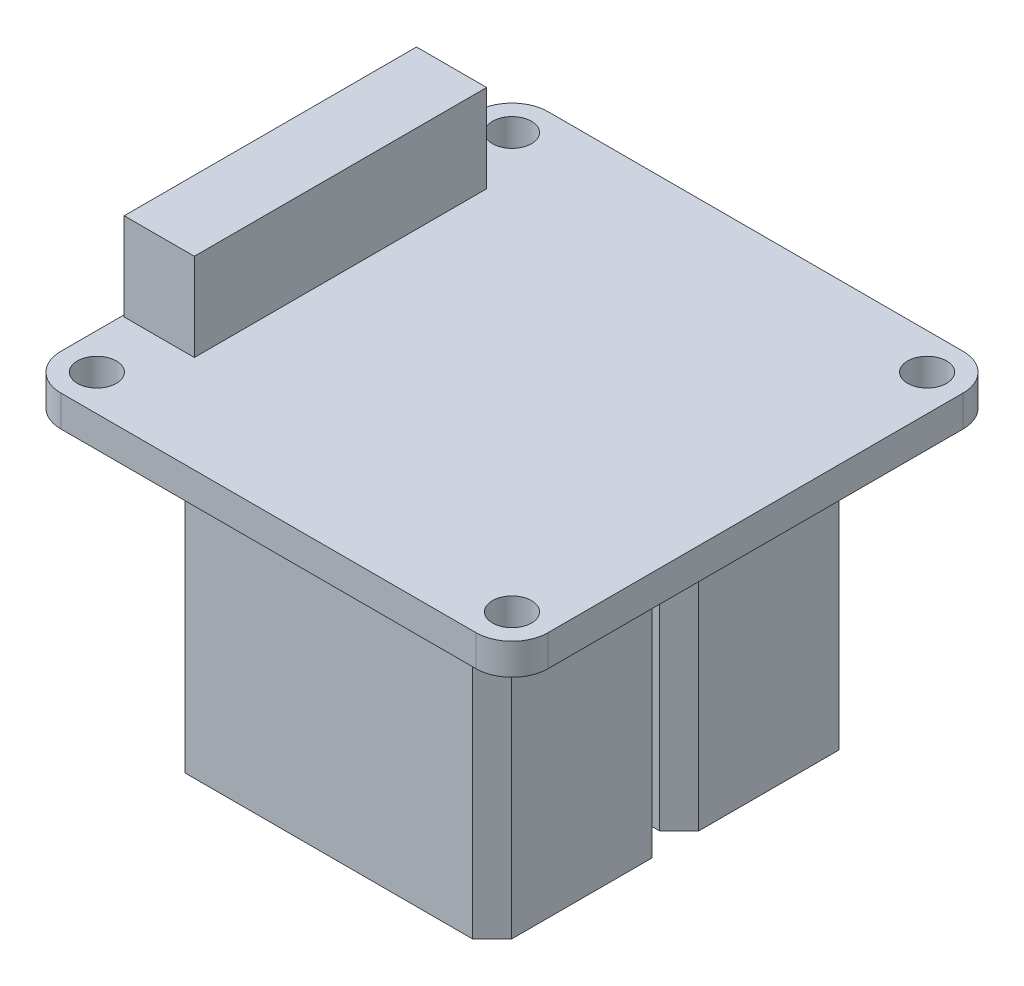
SolidWorks part; units mm, degrees
ref_plane "前视基准面" through (0, 0, 0) normal (0, 0, 1) x (1, 0, 0)
ref_plane "上视基准面" through (0, 0, 0) normal (0, 1, 0) x (1, 0, 0)
ref_plane "右视基准面" through (0, 0, 0) normal (1, 0, 0) x (0, 0, -1)
other "Configuration Table"
sketch "草图1" plane through (0, 0, 0) normal (0, 1, 0) x (1, 0, 0)
  line L1 (-10.65, 12.5) -> (10.65, 12.5)
  line L2 (-12.5, 10.65) -> (-12.5, -10.65)
  line L3 (-10.65, -12.5) -> (10.65, -12.5)
  line L4 (12.5, 10.65) -> (12.5, -10.65)
  line L5 (-12.5, 12.5) -> (12.5, -12.5) construction
  line L6 (-12.5, -12.5) -> (12.5, 12.5) construction
  arc A0 (12.5, 10.65) -> (10.65, 12.5) centre (10.65, 10.65) ccw
  arc A1 (10.65, -12.5) -> (12.5, -10.65) centre (10.65, -10.65) ccw
  arc A2 (-12.5, -10.65) -> (-10.65, -12.5) centre (-10.65, -10.65) ccw
  arc A3 (-10.65, 12.5) -> (-12.5, 10.65) centre (-10.65, 10.65) ccw
  circle A4 centre (-10.65, 10.65) radius 1
  circle A5 centre (-10.65, -10.65) radius 1
  circle A6 centre (10.65, -10.65) radius 1
  circle A7 centre (10.65, 10.65) radius 1
  point P0 (0, 0)
  dimension "D3" = 3.7
  dimension "D4" = 3.7
  dimension "D5" = 3.7
  dimension "D6" = 3.7
  dimension "D7" = 2
  dimension "D8" = 2
  dimension "D9" = 2
  dimension "D10" = 2
  dimension "D1" = 25
  dimension "D2" = 25
  dimension "D11" = 25
  dimension "D12" = 25
  dimension "D13" = 12.5
  dimension "D14" = 12.5
extrude "凸台-拉伸1" add sketch "草图1" along normal blind 1.6
sketch "草图2" plane through (0, 0, 0) normal (0, 1, 0) x (1, 0, 0)
  line L0 (-1000, 0) -> (49000, 0) construction
  line L1 (-8.38, 9.4) -> (8.38, 9.4)
  line L2 (-8.38, 9.4) -> (-8.38, 0.2)
  line L3 (-8.38, 0.2) -> (8.38, 0.2)
  line L4 (8.38, 9.4) -> (8.38, 0.2)
  line L5 (8.38, -9.4) -> (8.38, -0.2)
  line L6 (-8.38, -0.2) -> (8.38, -0.2)
  line L7 (-8.38, -9.4) -> (-8.38, -0.2)
  line L8 (-8.38, -9.4) -> (8.38, -9.4)
  point P4 (0, 0.2)
  dimension "D1" = 16.76
  dimension "D2" = 9.2
  dimension "D3" = 0.2
extrude "凸台-拉伸2" add sketch "草图2" against normal blind 15.2
sketch "草图3" plane through (0, 0, 0) normal (0, 1, 0) x (1, 0, 0)
  line L0 (-8.38, -0.2) -> (-8.38, -9.4) construction
  line L1 (-6.415, -5.6) -> (6.415, -5.6)
  line L2 (-6.415, -5.6) -> (-6.415, -4)
  line L3 (-6.415, -4) -> (6.415, -4)
  line L4 (6.415, -5.6) -> (6.415, -4)
  line L6 (8.38, -0.2) -> (-8.38, -0.2) construction
  line L7 (-1000, 0) -> (49000, 0) construction
  line L8 (6.415, 5.6) -> (6.415, 4)
  line L9 (-6.415, 4) -> (6.415, 4)
  line L10 (-6.415, 5.6) -> (-6.415, 4)
  line L11 (-6.415, 5.6) -> (6.415, 5.6)
  point P6 (-6.415, -4.8)
  point P9 (-8.38, -4.8)
  point P10 (0, -0.2)
  point P11 (0, -4)
  dimension "D1" = 1.6
  dimension "D2" = 12.83
extrude "切除-拉伸2" cut sketch "草图3" along normal blind 9 from surface at -15.2 starting at face at (0, -15.2, -4.8)
sketch "草图5" plane through (0, 0, 0) normal (0, 1, 0) x (1, 0, 0)
  line L0 (-8.38, -9.4) -> (-8.38, -8.4)
  line L1 (-8.38, -0.2) -> (-8.38, -9.4) construction
  line L2 (-8.38, -8.4) -> (-7.38, -9.4)
  line L3 (-8.38, -9.4) -> (8.38, -9.4) construction
  line L4 (-7.38, -9.4) -> (-8.38, -9.4)
  line L5 (7.38, -9.4) -> (8.38, -9.4)
  line L6 (8.38, -9.4) -> (8.38, -8.4)
  line L7 (8.38, -9.4) -> (8.38, -0.2) construction
  line L8 (8.38, -8.4) -> (7.38, -9.4)
  line L9 (-8.38, -0.2) -> (-8.38, -1.2)
  line L10 (-8.38, -0.2) -> (-8.38, -9.4) construction
  line L11 (-8.38, -1.2) -> (-7.38, -0.2)
  line L12 (8.38, -0.2) -> (-8.38, -0.2) construction
  line L13 (-7.38, -0.2) -> (-8.38, -0.2)
  line L14 (8.38, -0.2) -> (7.38, -0.2)
  line L15 (8.38, -0.2) -> (-8.38, -0.2) construction
  line L16 (7.38, -0.2) -> (8.38, -1.2)
  line L17 (8.38, -9.4) -> (8.38, -0.2) construction
  line L18 (8.38, -1.2) -> (8.38, -0.2)
  line L19 (-8.38, 0.2) -> (-7.38, 0.2)
  line L20 (-8.38, 0.2) -> (8.38, 0.2) construction
  line L21 (-7.38, 0.2) -> (-8.38, 1.2)
  line L22 (-8.38, 9.4) -> (-8.38, 0.2) construction
  line L23 (-8.38, 1.2) -> (-8.38, 0.2)
  line L24 (-8.38, 9.4) -> (-7.38, 9.4)
  line L25 (8.38, 9.4) -> (-8.38, 9.4) construction
  line L26 (-7.38, 9.4) -> (-8.38, 8.4)
  line L27 (-8.38, 9.4) -> (-8.38, 0.2) construction
  line L28 (-8.38, 8.4) -> (-8.38, 9.4)
  line L29 (8.38, 9.4) -> (7.38, 9.4)
  line L30 (8.38, 9.4) -> (-8.38, 9.4) construction
  line L31 (7.38, 9.4) -> (8.38, 8.4)
  line L32 (8.38, 0.2) -> (8.38, 9.4) construction
  line L33 (8.38, 8.4) -> (8.38, 9.4)
  line L34 (7.38, 0.2) -> (8.38, 0.2)
  line L35 (8.38, 0.2) -> (8.38, 1.2)
  line L36 (8.38, 1.2) -> (7.38, 0.2)
  dimension "D1" = 1
  dimension "D2" = 1
  dimension "D3" = 1
  dimension "D4" = 1
  dimension "D5" = 1
  dimension "D6" = 1
  dimension "D7" = 1
  dimension "D8" = 1
  dimension "D9" = 1
  dimension "D10" = 1
  dimension "D11" = 1
  dimension "D12" = 1
  dimension "D13" = 1
  dimension "D14" = 1
  dimension "D15" = 1
  dimension "D16" = 1
extrude "切除-拉伸3" cut sketch "草图5" along normal up to surface (15.2 mm away) from surface at -15.2 up to face at (0, 0, 4.8) starting at face at (0, -15.2, 4.8)
sketch "草图7" plane through (0, 0, 0) normal (0, 1, 0) x (1, 0, 0)
  line L0 (-12.5, 10.65) -> (-12.5, -10.65) construction
  line L1 (-12.4, 7.5) -> (-8.8, 7.5)
  line L2 (-12.4, 7.5) -> (-12.4, -7.5)
  line L3 (-12.4, -7.5) -> (-8.8, -7.5)
  line L4 (-8.8, 7.5) -> (-8.8, -7.5)
  point P6 (-12.5, 0)
  point P7 (-12.4, 0)
  dimension "D1" = 15
  dimension "D2" = 3.6
  dimension "D3" = 0.1
extrude "凸台-拉伸4" add sketch "草图7" along normal blind 4.5 from surface at 1.6 starting at face at (10.65, 1.6, 11.65)
